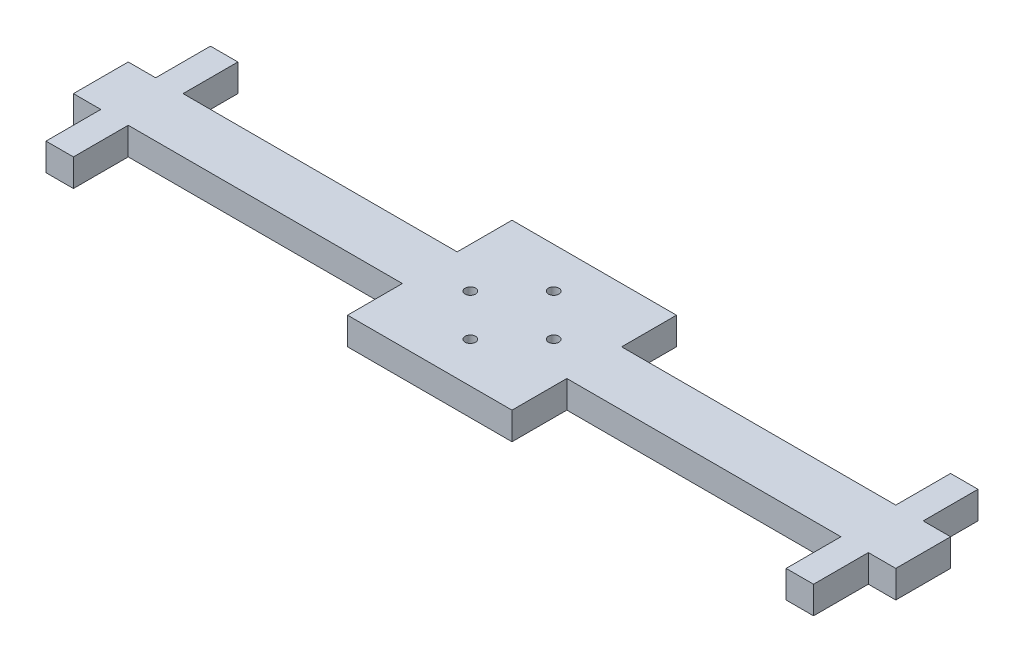
SolidWorks part; units mm, degrees
ref_plane "Front Plane" through (0, 0, 0) normal (0, 0, 1) x (1, 0, 0)
ref_plane "Top Plane" through (0, 0, 0) normal (0, 1, 0) x (1, 0, 0)
ref_plane "Right Plane" through (0, 0, 0) normal (1, 0, 0) x (0, 0, -1)
sketch "Sketch1" plane through (0, 0, 0) normal (0, 1, 0) x (1, 0, 0)
  line L0 (0, 0) -> (0, 12.7)
  line L1 (0, 12.7) -> (6.35, 12.7)
  line L2 (6.35, 12.7) -> (6.35, 25.4)
  line L3 (6.35, 25.4) -> (12.7, 25.4)
  line L4 (12.7, 25.4) -> (12.7, 12.7)
  line L5 (12.7, 12.7) -> (76.2, 12.7)
  line L6 (76.2, 12.7) -> (76.2, 25.4)
  line L7 (76.2, 25.4) -> (114.3, 25.4)
  line L8 (114.3, 25.4) -> (114.3, 12.7)
  line L9 (114.3, 12.7) -> (177.8, 12.7)
  line L10 (177.8, 12.7) -> (177.8, 25.4)
  line L11 (177.8, 25.4) -> (184.15, 25.4)
  line L12 (184.15, 25.4) -> (184.15, 12.7)
  line L13 (184.15, 12.7) -> (190.5, 12.7)
  line L14 (190.5, 12.7) -> (190.5, 0)
  line L15 (190.5, 0) -> (184.15, 0)
  line L16 (184.15, 0) -> (184.15, -12.7)
  line L17 (184.15, -12.7) -> (177.8, -12.7)
  line L18 (177.8, -12.7) -> (177.8, 0)
  line L19 (177.8, 0) -> (114.3, 0)
  line L20 (114.3, 0) -> (114.3, -12.7)
  line L21 (114.3, -12.7) -> (76.2, -12.7)
  line L22 (76.2, -12.7) -> (76.2, 0)
  line L23 (76.2, 0) -> (12.7, 0)
  line L24 (12.7, 0) -> (12.7, -12.7)
  line L25 (12.7, -12.7) -> (6.35, -12.7)
  line L26 (6.35, -12.7) -> (6.35, 0)
  line L27 (6.35, 0) -> (0, 0)
  line L28 (95.25, 25.4) -> (95.25, -12.7) construction
  line L29 (95.25, 6.35) -> (104.902, 6.35) construction
  line L30 (95.25, 6.35) -> (85.598, 6.35) construction
  line L31 (95.25, 16.002) -> (95.25, 6.35) construction
  line L32 (95.25, 16.002) -> (97.6387, 16.002) construction
  line L33 (97.6387, 16.002) -> (97.6387, 6.35) construction
  line L34 (95.25, -3.302) -> (99.404, -3.302) construction
  line L35 (99.404, -3.302) -> (99.404, 6.35) construction
  circle A0 centre (85.598, 6.35) radius 1.2065
  circle A1 centre (104.902, 6.35) radius 1.2065
  circle A2 centre (95.25, 16.002) radius 1.2065
  circle A3 centre (95.25, -3.302) radius 1.2065
  point P31 (95.25, 25.4)
  dimension "D9" = 2.413
  dimension "D1" = 38.1
  dimension "D2" = 38.1
  dimension "D3" = 12.7
  dimension "D4" = 6.35
  dimension "D5" = 12.7
  dimension "D6" = 6.35
  dimension "D7" = 63.5
  dimension "D8" = 9.652
  dimension "D10" = 9.652
  dimension "D11" = 9.652
extrude "Boss-Extrude1" add sketch "Sketch1" along normal blind 6.35
